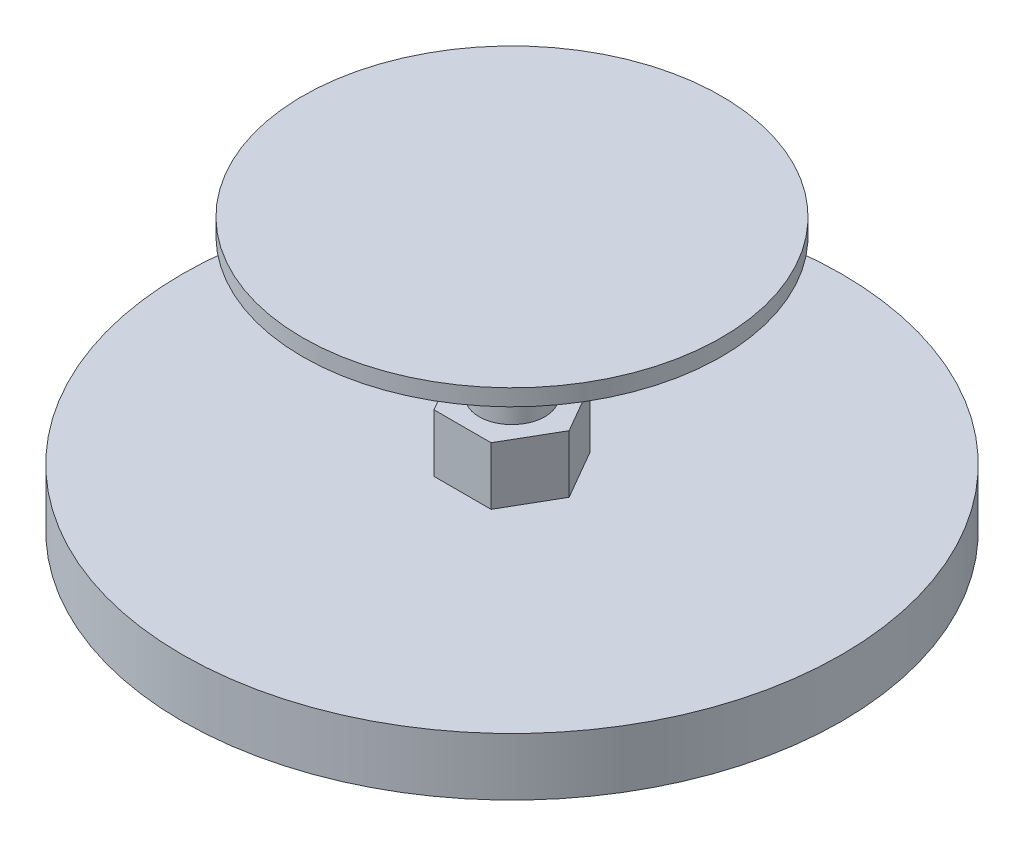
SolidWorks part; units mm, degrees
ref_plane "Plano frontal" through (0, 0, 0) normal (0, 0, 1) x (1, 0, 0)
ref_plane "Plano superior" through (0, 0, 0) normal (0, 1, 0) x (1, 0, 0)
ref_plane "Plano direito" through (0, 0, 0) normal (1, 0, 0) x (0, 0, -1)
sketch "Esboço2" plane through (0, 0, 0) normal (0, 1, 0) x (1, 0, 0)
  circle A0 centre (0, 0) radius 40
  dimension "D1" = 80
extrude "Ressalto-extrusão1" add sketch "Esboço2" along normal blind 7
sketch "Esboço3" plane through (0, 7, 0) normal (0, 1, 0) x (1, 0, 0)
  line L1 (6.9282, 0) -> (3.4641, 6)
  line L2 (3.4641, 6) -> (-3.4641, 6)
  line L3 (-3.4641, 6) -> (-6.9282, 0)
  line L4 (-6.9282, 0) -> (-3.4641, -6)
  line L5 (-3.4641, -6) -> (3.4641, -6)
  line L6 (3.4641, -6) -> (6.9282, 0)
  circle A0 centre (0, 0) radius 6 construction
  dimension "D1" = 12
extrude "Ressalto-extrusão2" add sketch "Esboço3" along normal blind 7
sketch "Esboço4" plane through (0, 14, 0) normal (0, 1, 0) x (1, 0, 0)
  circle A0 centre (0, 0) radius 4
  dimension "D1" = 8
extrude "Ressalto-extrusão3" add sketch "Esboço4" along normal blind 10
sketch "Esboço5" plane through (0, 24, 0) normal (0, 1, 0) x (1, 0, 0)
  line L1 (6.9282, 0) -> (3.4641, 6)
  line L2 (3.4641, 6) -> (-3.4641, 6)
  line L3 (-3.4641, 6) -> (-6.9282, 0)
  line L4 (-6.9282, 0) -> (-3.4641, -6)
  line L5 (-3.4641, -6) -> (3.4641, -6)
  line L6 (3.4641, -6) -> (6.9282, 0)
  circle A0 centre (0, 0) radius 6 construction
extrude "Ressalto-extrusão4" add sketch "Esboço5" along normal blind 7
sketch "Esboço6" plane through (0, 31, 0) normal (0, 1, 0) x (1, 0, 0)
  circle A0 centre (0, 0) radius 25.4
  dimension "D1" = 50.8
extrude "Ressalto-extrusão5" add sketch "Esboço6" along normal blind 2
